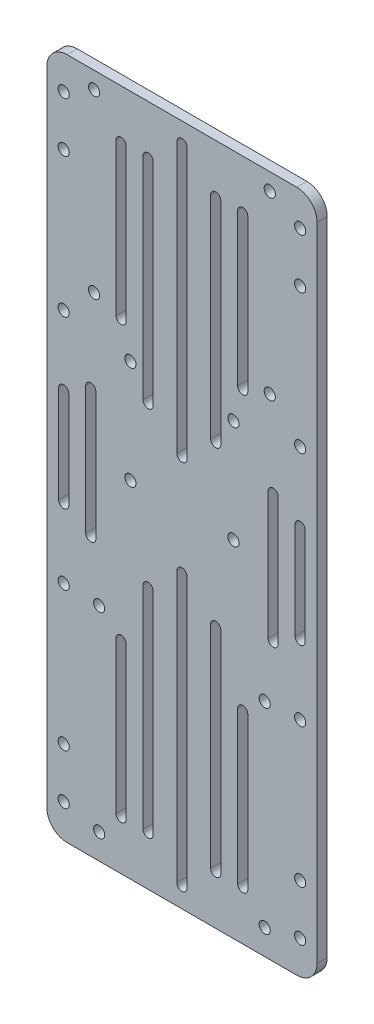
SolidWorks part; units mm, degrees
ref_plane "Спереди" through (0, 0, 0) normal (0, 0, 1) x (1, 0, 0)
ref_plane "Сверху" through (0, 0, 0) normal (0, 1, 0) x (1, 0, 0)
ref_plane "Справа" through (0, 0, 0) normal (1, 0, 0) x (0, 0, -1)
sketch "Эскиз1" plane through (0, 0, 0) normal (0, 0, 1) x (1, 0, 0)
  line L0 (-357.5893, 0) -> (17521.8739, 0) construction
  line L1 (0, -357.5893) -> (0, 17521.8739) construction
  line L3 (-34, 101) -> (34, 101)
  line L4 (-40, 95) -> (-40, -95)
  line L5 (-34, -101) -> (34, -101)
  line L6 (40, 95) -> (40, -95)
  circle A0 centre (-35, 91) radius 1.65
  circle A1 centre (-35, 35) radius 1.65
  arc A2 (-40, -95) -> (-34, -101) centre (-34, -95) ccw
  arc A3 (34, -101) -> (40, -95) centre (34, -95) ccw
  arc A4 (34, 101) -> (40, 95) centre (34, 95) cw
  arc A5 (-40, 95) -> (-34, 101) centre (-34, 95) cw
  circle A6 centre (35, 35) radius 1.65
  circle A7 centre (35, 91) radius 1.65
  circle A8 centre (35, -91) radius 1.65
  circle A9 centre (-35, -91) radius 1.65
  circle A10 centre (-35, -35) radius 1.65
  circle A11 centre (35, -35) radius 1.65
  point P13 (0, 0)
  point P14 (-13.2348, 9.1589)
  point P15 (-33.2188, 94.0721)
  point P16 (-33.3538, 92.7349)
  point P21 (40, -101)
  point P24 (40, 101)
  point P27 (-40, 101)
  dimension "D1" = 3.3
  dimension "D7" = 6
  dimension "D2" = 80
  dimension "D3" = 202
  dimension "D4" = 35
  dimension "D5" = 10
  dimension "D6" = 5
extrude "Бобышка-Вытянуть1" add sketch "Эскиз1" along normal blind 3
sketch "Эскиз3" plane through (0, 0, 3) normal (0, 0, 1) x (1, 0, 0)
  line L0 (-1000, 0) -> (49000, 0) construction
  line L1 (0, -1000) -> (0, 49000) construction
  line L2 (-26, 96) -> (26, 44) construction
  line L3 (-26, 96) -> (26, 96) construction
  line L4 (-26, 96) -> (-26, 44) construction
  line L5 (-26, 44) -> (26, 44) construction
  line L6 (26, 96) -> (26, 44) construction
  line L7 (-22.5, 39) -> (22.5, 39) construction
  line L8 (-22.5, 39) -> (-22.5, -6) construction
  line L9 (-22.5, -6) -> (22.5, -6) construction
  line L10 (22.5, 39) -> (22.5, -6) construction
  line L11 (-28, -12) -> (28, -12) construction
  line L12 (-15.25, 31.75) -> (15.25, 31.75) construction
  line L13 (-15.25, 31.75) -> (-15.25, 1.25) construction
  line L14 (-15.25, 1.25) -> (15.25, 1.25) construction
  line L15 (15.25, 31.75) -> (15.25, 1.25) construction
  line L16 (-28, -12) -> (-28, -97) construction
  line L17 (-28, -97) -> (28, -97) construction
  line L18 (28, -12) -> (28, -97) construction
  line L19 (-24.5, -35.5) -> (24.5, -35.5) construction
  line L20 (-24.5, -35.5) -> (-24.5, -93.5) construction
  line L21 (-24.5, -93.5) -> (24.5, -93.5) construction
  line L22 (24.5, -35.5) -> (24.5, -93.5) construction
  line L23 (-26, 44) -> (26, 96) construction
  line L24 (22.5, 39) -> (-22.5, -6) construction
  line L25 (-22.5, 39) -> (22.5, -6) construction
  circle A0 centre (-24.5, -93.5) radius 1.65
  circle A1 centre (-24.5, -35.5) radius 1.65
  circle A2 centre (-15.25, 1.25) radius 1.65
  circle A3 centre (-15.25, 31.75) radius 1.65
  circle A4 centre (-26, 44) radius 1.65
  circle A5 centre (-26, 96) radius 1.65
  circle A6 centre (24.5, -93.5) radius 1.65
  circle A7 centre (24.5, -35.5) radius 1.65
  circle A8 centre (15.25, 1.25) radius 1.65
  circle A9 centre (15.25, 31.75) radius 1.65
  circle A10 centre (26, 44) radius 1.65
  circle A11 centre (26, 96) radius 1.65
  point P25 (0, 70)
  point P26 (0, 16.5)
  dimension "D12" = 3.3
  dimension "D1" = 52
  dimension "D2" = 45
  dimension "D3" = 30.5
  dimension "D4" = 85
  dimension "D5" = 58
  dimension "D6" = 5
  dimension "D7" = 5
  dimension "D8" = 6
  dimension "D9" = 49
  dimension "D10" = 3.5
  dimension "D11" = 56
extrude "Вырез-Вытянуть2" cut sketch "Эскиз3" against normal through all
sketch "Эскиз4" plane through (0, 0, 3) normal (0, 0, 1) x (1, 0, 0)
  line L0 (-1000, 0) -> (49000, 0) construction
  line L1 (0, -1000) -> (0, 49000) construction
  circle A0 centre (-35, 76.19) radius 1.65
  circle A1 centre (-35, 91) radius 1.65 construction
  circle A2 centre (35, 76.19) radius 1.65
  circle A3 centre (35, -76.19) radius 1.65
  circle A4 centre (-35, -76.19) radius 1.65
  point P9 (0, 0)
  point P12 (-35, 91)
  dimension "D1" = 76.19
extrude "Вырез-Вытянуть3" cut sketch "Эскиз4" against normal through all
sketch "Эскиз5" plane through (0, 0, 3) normal (0, 0, 1) x (1, 0, 0)
  line L0 (-1000, 0) -> (49000, 0) construction
  line L1 (0, -1000) -> (0, 49000) construction
  line L2 (-35, 14.365) -> (-35, -14.365) construction
  line L3 (-33.5, 14.365) -> (-33.5, -14.365)
  line L4 (-36.5, 14.365) -> (-36.5, -14.365)
  line L5 (-26.99, 18.895) -> (-26.99, -18.895) construction
  line L6 (-25.49, 18.895) -> (-25.49, -18.895)
  line L7 (-28.49, 18.895) -> (-28.49, -18.895)
  line L8 (-18, -41.32) -> (-18, -86.32) construction
  line L9 (-16.5, -41.32) -> (-16.5, -86.32)
  line L10 (-19.5, -41.32) -> (-19.5, -86.32)
  line L11 (-10, -23.74) -> (-10, -86.32) construction
  line L12 (-8.5, -23.74) -> (-8.5, -86.32)
  line L13 (-11.5, -23.74) -> (-11.5, -86.32)
  line L14 (0, -15.03) -> (0, -95.03) construction
  line L15 (1.5, -15.03) -> (1.5, -95.03)
  line L16 (-1.5, -15.03) -> (-1.5, -95.03)
  line L17 (10, -23.74) -> (10, -86.32) construction
  line L18 (8.5, -23.74) -> (8.5, -86.32)
  line L19 (11.5, -23.74) -> (11.5, -86.32)
  line L20 (18, -41.32) -> (18, -86.32) construction
  line L21 (16.5, -41.32) -> (16.5, -86.32)
  line L22 (19.5, -41.32) -> (19.5, -86.32)
  line L23 (26.99, 18.895) -> (26.99, -18.895) construction
  line L24 (25.49, 18.895) -> (25.49, -18.895)
  line L25 (28.49, 18.895) -> (28.49, -18.895)
  line L26 (35, 14.365) -> (35, -14.365) construction
  line L27 (33.5, 14.365) -> (33.5, -14.365)
  line L28 (36.5, 14.365) -> (36.5, -14.365)
  line L29 (-18, 41.32) -> (-18, 86.32) construction
  line L30 (-16.5, 41.32) -> (-16.5, 86.32)
  line L31 (-19.5, 41.32) -> (-19.5, 86.32)
  line L32 (-10, 23.74) -> (-10, 86.32) construction
  line L33 (-8.5, 23.74) -> (-8.5, 86.32)
  line L34 (-11.5, 23.74) -> (-11.5, 86.32)
  line L35 (10, 23.74) -> (10, 86.32) construction
  line L36 (8.5, 23.74) -> (8.5, 86.32)
  line L37 (11.5, 23.74) -> (11.5, 86.32)
  line L38 (18, 41.32) -> (18, 86.32) construction
  line L39 (16.5, 41.32) -> (16.5, 86.32)
  line L40 (19.5, 41.32) -> (19.5, 86.32)
  line L41 (0, 15.03) -> (0, 95.03) construction
  line L42 (1.5, 15.03) -> (1.5, 95.03)
  line L43 (-1.5, 15.03) -> (-1.5, 95.03)
  arc A0 (-33.5, 14.365) -> (-36.5, 14.365) centre (-35, 14.365) ccw
  arc A1 (-36.5, -14.365) -> (-33.5, -14.365) centre (-35, -14.365) ccw
  arc A2 (-25.49, 18.895) -> (-28.49, 18.895) centre (-26.99, 18.895) ccw
  arc A3 (-28.49, -18.895) -> (-25.49, -18.895) centre (-26.99, -18.895) ccw
  arc A4 (-16.5, -41.32) -> (-19.5, -41.32) centre (-18, -41.32) ccw
  arc A5 (-19.5, -86.32) -> (-16.5, -86.32) centre (-18, -86.32) ccw
  arc A6 (-8.5, -23.74) -> (-11.5, -23.74) centre (-10, -23.74) ccw
  arc A7 (-11.5, -86.32) -> (-8.5, -86.32) centre (-10, -86.32) ccw
  arc A8 (1.5, -15.03) -> (-1.5, -15.03) centre (0, -15.03) ccw
  arc A9 (-1.5, -95.03) -> (1.5, -95.03) centre (0, -95.03) ccw
  arc A10 (8.5, -23.74) -> (11.5, -23.74) centre (10, -23.74) cw
  arc A11 (11.5, -86.32) -> (8.5, -86.32) centre (10, -86.32) cw
  arc A12 (16.5, -41.32) -> (19.5, -41.32) centre (18, -41.32) cw
  arc A13 (19.5, -86.32) -> (16.5, -86.32) centre (18, -86.32) cw
  arc A14 (25.49, 18.895) -> (28.49, 18.895) centre (26.99, 18.895) cw
  arc A15 (28.49, -18.895) -> (25.49, -18.895) centre (26.99, -18.895) cw
  arc A16 (33.5, 14.365) -> (36.5, 14.365) centre (35, 14.365) cw
  arc A17 (36.5, -14.365) -> (33.5, -14.365) centre (35, -14.365) cw
  arc A18 (-16.5, 41.32) -> (-19.5, 41.32) centre (-18, 41.32) cw
  arc A19 (-19.5, 86.32) -> (-16.5, 86.32) centre (-18, 86.32) cw
  arc A20 (-8.5, 23.74) -> (-11.5, 23.74) centre (-10, 23.74) cw
  arc A21 (-11.5, 86.32) -> (-8.5, 86.32) centre (-10, 86.32) cw
  arc A22 (8.5, 23.74) -> (11.5, 23.74) centre (10, 23.74) ccw
  arc A23 (11.5, 86.32) -> (8.5, 86.32) centre (10, 86.32) ccw
  arc A24 (16.5, 41.32) -> (19.5, 41.32) centre (18, 41.32) ccw
  arc A25 (19.5, 86.32) -> (16.5, 86.32) centre (18, 86.32) ccw
  arc A26 (1.5, 15.03) -> (-1.5, 15.03) centre (0, 15.03) cw
  arc A27 (-1.5, 95.03) -> (1.5, 95.03) centre (0, 95.03) cw
  point P7 (-35, 0)
  point P12 (-26.99, 0)
  point P21 (-18, -63.82)
  point P26 (-10, -55.03)
  point P33 (0, -55.03)
  point P42 (10, -55.03)
  point P49 (18, -63.82)
  point P56 (26.99, 0)
  point P63 (35, 0)
  point P70 (-18, 63.82)
  point P77 (-10, 55.03)
  point P84 (10, 55.03)
  point P91 (18, 63.82)
  point P98 (0, 55.03)
  point P103 (0, 0)
  point P104 (0, 0)
  point P105 (0, 0)
  point P106 (-35, 35)
  point P107 (0, 0)
  point P110 (0, -51.2171)
  point P111 (0, 0)
  dimension "D11" = 1.5
  dimension "D2" = 8.01
  dimension "D3" = 37.79
  dimension "D4" = 28.73
  dimension "D5" = 10
  dimension "D6" = 8
  dimension "D7" = 37.18
  dimension "D8" = 80
  dimension "D9" = 62.58
  dimension "D10" = 45
extrude "Вырез-Вытянуть4" cut sketch "Эскиз5" against normal through all
